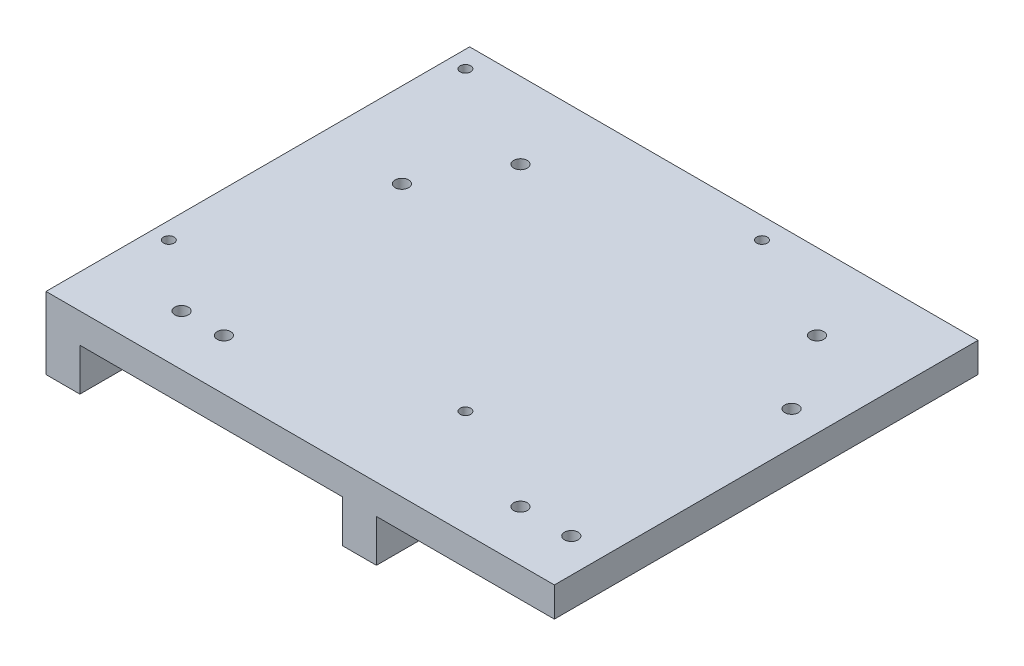
SolidWorks part; units mm, degrees
ref_plane "前视基准面" through (0, 0, 0) normal (0, 0, 1) x (1, 0, 0)
ref_plane "上视基准面" through (0, 0, 0) normal (0, 1, 0) x (1, 0, 0)
ref_plane "右视基准面" through (0, 0, 0) normal (1, 0, 0) x (0, 0, -1)
other "Configuration Table"
sketch "草图1" plane through (0, 0, 0) normal (0, 1, 0) x (1, 0, 0)
  line L1 (-50, 50) -> (70, 50)
  line L2 (-50, 50) -> (-50, -50)
  line L3 (-50, -50) -> (70, -50)
  line L4 (70, 50) -> (70, -50)
  point P0 (0, 0)
  dimension "D1" = 120
  dimension "D2" = 100
extrude "凸台-拉伸1" add sketch "草图1" along normal blind 7
sketch "草图2" plane through (0, 0, 0) normal (0, -1, 0) x (1, 0, 0)
  line L0 (-50, 50) -> (70, 50) construction
  line L1 (70, 50) -> (70, -50) construction
  circle A0 centre (62, 38) radius 2.8
  circle A1 centre (-30, 38) radius 2.8
  circle A2 centre (-30, -14) radius 2.8
  circle A3 centre (62, -14) radius 2.8
  circle A8 centre (-20, 38) radius 2.8
  circle A9 centre (50, 38) radius 2.8
  circle A10 centre (50, -32) radius 2.8
  circle A11 centre (-20, -32) radius 2.8
  dimension "D1" = 5.6
  dimension "D6" = 2
  dimension "D4" = 12
  dimension "D5" = 8
  dimension "D7" = 2
  dimension "D8" = 2
  dimension "D9" = 92
  dimension "D10" = 52
  dimension "D2" = 2
  dimension "D3" = 2
extrude "切除-拉伸1" cut sketch "草图2" against normal blind 4
sketch "草图3" plane through (0, 4, 0) normal (0, -1, 0) x (1, 0, 0)
  circle A0 centre (62, 38) radius 1.6
  circle A1 centre (-30, 38) radius 1.6
  circle A2 centre (-30, -14) radius 1.6
  circle A3 centre (62, -14) radius 1.6
  circle A7 centre (-20, 38) radius 1.6
  circle A8 centre (50, 38) radius 1.6
  circle A9 centre (50, -32) radius 1.6
  circle A10 centre (-20, -32) radius 1.6
  dimension "D1" = 3.2
  dimension "D2" = 2
  dimension "D3" = 2
  dimension "D4" = 2
  dimension "D5" = 2
  dimension "D6" = 2
extrude "切除-拉伸2" cut sketch "草图3" against normal up to next
sketch "草图4" plane through (0, 0, 0) normal (0, -1, 0) x (1, 0, 0)
  line L0 (-50, 50) -> (70, 50) construction
  line L1 (-50, -50) -> (-42, -50)
  line L2 (-50, -50) -> (-50, 50)
  line L3 (-50, 50) -> (-42, 50)
  line L4 (-42, -50) -> (-42, 50)
  line L5 (20, -50) -> (20, 50)
  line L6 (20, -50) -> (28, -50)
  line L7 (28, -50) -> (28, 50)
  line L8 (20, 50) -> (28, 50)
  point P7 (-46, -50)
  dimension "D1" = 8
  dimension "D2" = 100
  dimension "D3" = 2
extrude "凸台-拉伸2" add sketch "草图4" along normal blind 10
sketch "草图9" plane through (0, -10, 0) normal (0, -1, 0) x (1, 0, 0)
  line L0 (-42, -50) -> (-42, 50) construction
  line L1 (-50, -50) -> (-42, -50) construction
  circle A0 centre (-46, -45) radius 1.5
  circle A1 centre (24, -45) radius 1.5
  circle A2 centre (24, 25) radius 1.5
  circle A3 centre (-46, 25) radius 1.5
  point P0 (-46, -45)
  point P9 (24, -45)
  point P11 (24, 25)
  point P13 (-46, 25)
  dimension "D2" = 3
  dimension "D1" = 4
  dimension "D3" = 5
  dimension "D4" = 2
  dimension "D5" = 2
hole_wizard "M3 螺纹孔5" positions "草图9" profile "草图10" tap size "M3" standard "GB" end condition up to next
sketch "草图10" plane through (-46, -10, -45) normal (1, 0, 0) x (0, 0, -1)
  line L0 (0, 0) -> (0, 17)
  line L1 (0, 17) -> (1.25, 17)
  line L2 (1.25, 17) -> (1.25, 0.275)
  line L3 (1.25, 0.275) -> (1.525, 0)
  line L5 (1.525, 0) -> (0, 0)
  line L6 (-1.25, 0.275) -> (-1.525, 0) construction
  line L11 (0, -6.35) -> (0, 107.95) construction
  dimension "通孔螺纹孔钻头直径" = 2.5
  dimension "通孔螺纹孔钻头深度" = 17
  dimension "近端锥形沉头孔直径" = 3.05
  dimension "近端锥形沉头孔角度" = 90
cosmetic thread "孔螺蚊线5" parameters "D2"=3
cosmetic thread "孔螺蚊线6" parameters "D2"=3
cosmetic thread "孔螺蚊线7" parameters "D2"=3
cosmetic thread "孔螺蚊线8" parameters "D2"=3
